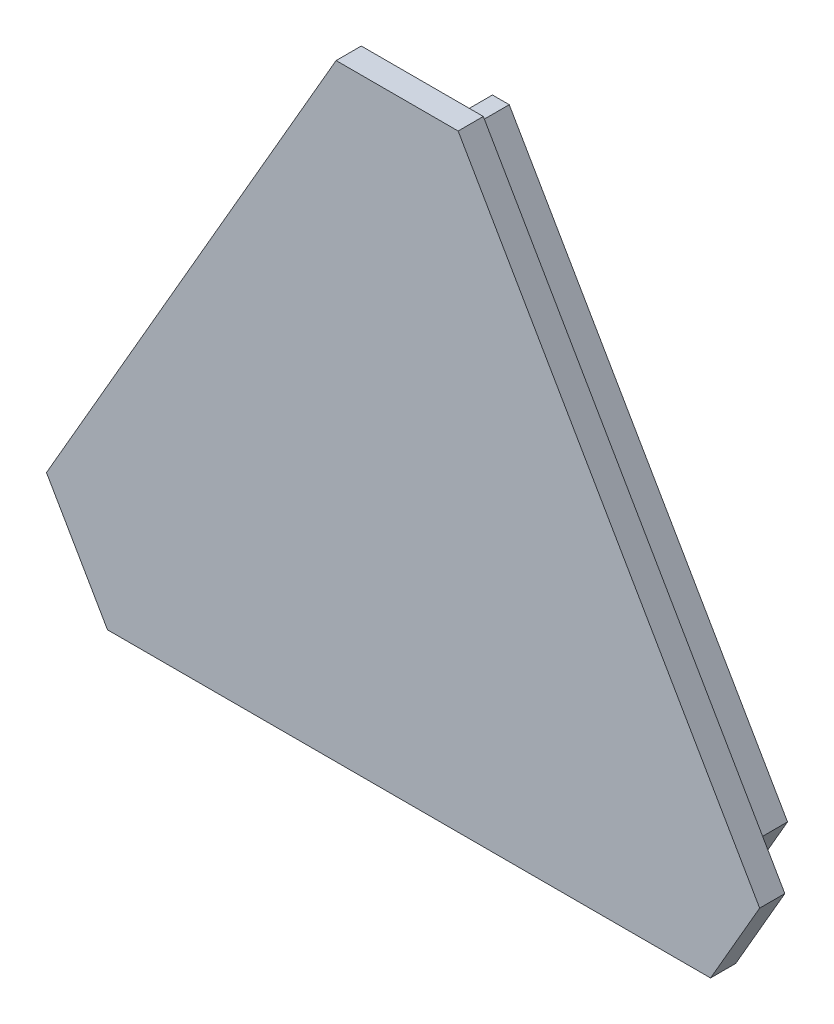
SolidWorks part; units mm, degrees
ref_plane "Front Plane" through (0, 0, 0) normal (0, 0, 1) x (1, 0, 0)
ref_plane "Top Plane" through (0, 0, 0) normal (0, 1, 0) x (1, 0, 0)
ref_plane "Right Plane" through (0, 0, 0) normal (1, 0, 0) x (0, 0, -1)
sketch "Sketch2" plane through (0, 0, 0) normal (0, 0, 1) x (1, 0, 0)
  line L0 (77.7691, 108.7192) -> (133.0381, 12.9904)
  line L1 (133.0381, 12.9904) -> (125.7691, 0.4)
  line L2 (125.7691, 0.4) -> (15.2309, 0.4)
  line L3 (78, 109.1192) -> (133.5, 12.9904) construction
  line L4 (133.5, 12.9904) -> (126, 0) construction
  line L5 (126, 0) -> (15, 0) construction
  line L7 (15.2309, 0.4) -> (13.5622, 3.2904)
  line L8 (13.5622, 3.2904) -> (14.7802, 5.4)
  line L9 (15, 0) -> (13.1003, 3.2904) construction
  line L10 (28.3254, 29.6611) -> (13.1003, 3.2904) construction
  line L11 (14.7802, 5.4) -> (122.8823, 5.4)
  line L12 (122.8823, 5.4) -> (127.2646, 12.9904)
  line L13 (127.2646, 12.9904) -> (73.2135, 106.6096)
  line L14 (77.7691, 108.7192) -> (74.4315, 108.7192)
  line L15 (74.4315, 108.7192) -> (73.2135, 106.6096)
  line L16 (74.2006, 109.1192) -> (58.9754, 82.7485) construction
  line L17 (74.2006, 109.1192) -> (78, 109.1192) construction
  dimension "D6" = 5
  dimension "D7" = 5
  dimension "D8" = 5
extrude "Boss-Extrude1" add sketch "Sketch2" against normal blind 10
sketch "Sketch3" plane through (0, 0, 0) normal (0, 0, 1) x (1, 0, 0)
  line L0 (58.3812, 114.1192) -> (82.6188, 114.1192)
  line L1 (82.6188, 114.1192) -> (142.5042, 10.3947)
  line L2 (142.5042, 10.3947) -> (132.75, -6.5)
  line L3 (132.75, -6.5) -> (12.9793, -6.5)
  line L4 (12.9793, -6.5) -> (0.8605, 14.4904)
  line L5 (0.8605, 14.4904) -> (58.3812, 114.1192)
extrude "Boss-Extrude2" add sketch "Sketch3" along normal blind 5
equation "\"gap\"= 0.4"
